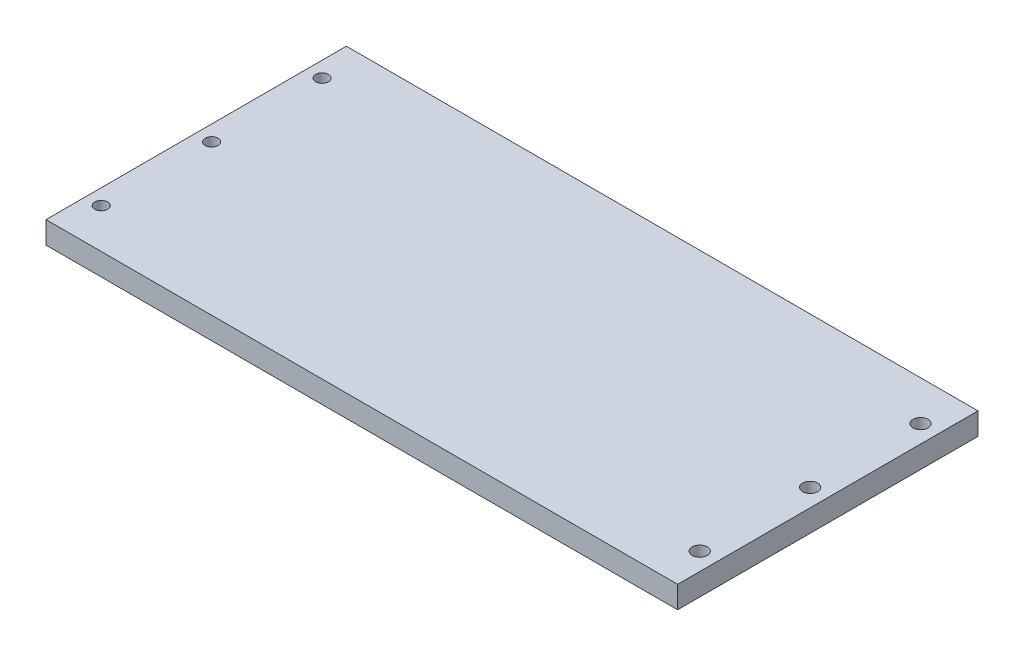
SolidWorks part; units mm, degrees
ref_plane "前基準面" through (0, 0, 0) normal (0, 0, 1) x (1, 0, 0)
ref_plane "上基準面" through (0, 0, 0) normal (0, 1, 0) x (1, 0, 0)
ref_plane "右基準面" through (0, 0, 0) normal (1, 0, 0) x (0, 0, -1)
sketch "草圖1" plane through (0, 0, 0) normal (0, 1, 0) x (1, 0, 0)
  line L1 (-71.5, -34) -> (71.5, -34)
  line L2 (-71.5, -34) -> (-71.5, 34)
  line L3 (-71.5, 34) -> (71.5, 34)
  line L4 (71.5, -34) -> (71.5, 34)
  line L5 (-71.5, -34) -> (71.5, 34) construction
  line L6 (-71.5, 34) -> (71.5, -34) construction
  point P0 (0, 0)
  dimension "D1" = 143
  dimension "D2" = 68
extrude "填料-伸長1" add sketch "草圖1" along normal blind 5
hole_wizard "M2.5 錐坑平頭螺釘的錐孔1" positions "草圖2" profile "草圖3" countersink size "M2.5" standard "ISO" end condition through all
sketch "草圖2" plane through (0, 0, 0) normal (0, -1, 0) x (-1, 0, 0)
  point P0 (68, 25)
  point P2 (68, 0)
  point P4 (68, -25)
  dimension "D1" = 25
  dimension "D2" = 25
  dimension "D3" = 68
sketch "草圖3" plane through (-68, 0, -25) normal (1, 0, 0) x (0, 0, -1)
  line L0 (0, 0) -> (0, 5)
  line L1 (0, 5) -> (1.45, 5)
  line L2 (1.45, 5) -> (1.45, 1.3)
  line L3 (1.45, 1.3) -> (2.75, 0)
  line L5 (2.75, 0) -> (0, 0)
  line L6 (-1.45, 1.3) -> (-2.75, 0) construction
  line L11 (0, -6.35) -> (0, 107.95) construction
  dimension "貫穿孔直徑" = 2.9
  dimension "貫穿孔深度" = 5
  dimension "近端錐孔直徑" = 5.5
  dimension "近端錐孔角度" = 90
hole_wizard "M3 錐坑平頭螺釘的錐孔1" positions "草圖4" profile "草圖5" countersink size "M3" standard "ISO" end condition through all
sketch "草圖4" plane through (0, 0, 0) normal (0, -1, 0) x (-1, 0, 0)
  point P0 (-67.5, 25)
  point P2 (-67.5, 0)
  point P4 (-67.5, -25)
  point P7 (0, 0)
  dimension "D1" = 67.5
  dimension "D2" = 25
  dimension "D3" = 25
sketch "草圖5" plane through (67.5, 0, -25) normal (1, 0, 0) x (0, 0, -1)
  line L0 (0, 0) -> (0, 5)
  line L1 (0, 5) -> (1.7, 5)
  line L2 (1.7, 5) -> (1.7, 1.45)
  line L3 (1.7, 1.45) -> (3.15, 0)
  line L5 (3.15, 0) -> (0, 0)
  line L6 (-1.7, 1.45) -> (-3.15, 0) construction
  line L11 (0, -6.35) -> (0, 107.95) construction
  dimension "貫穿孔直徑" = 3.4
  dimension "貫穿孔深度" = 5
  dimension "近端錐孔直徑" = 6.3
  dimension "近端錐孔角度" = 90
